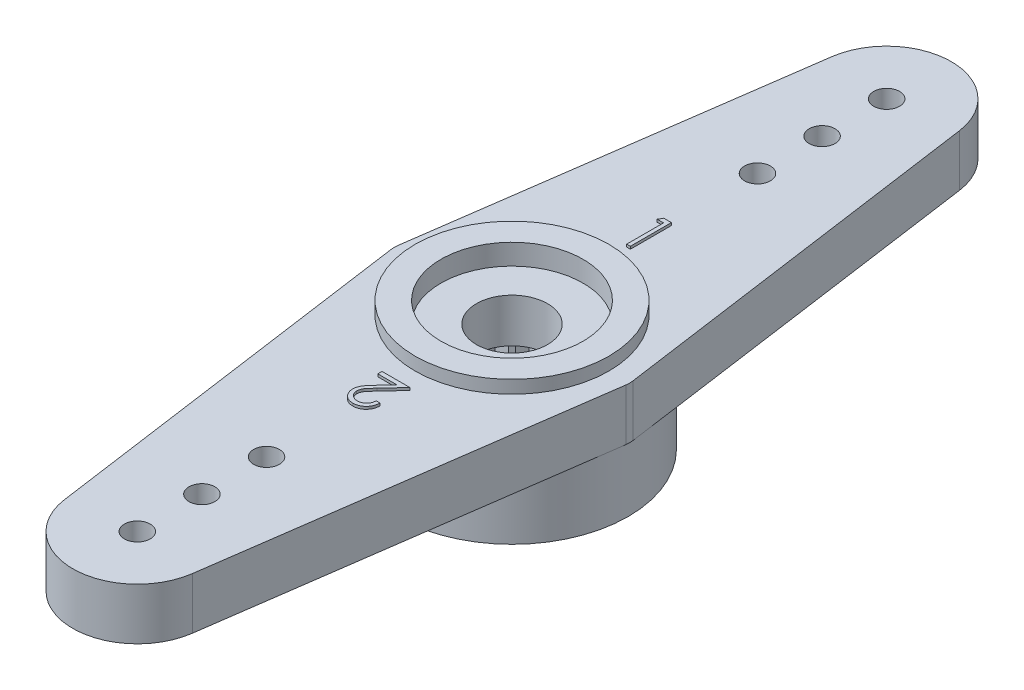
SolidWorks part; units mm, degrees
ref_plane "Front Plane" through (0, 0, 0) normal (0, 0, 1) x (1, 0, 0)
ref_plane "Top Plane" through (0, 0, 0) normal (0, 1, 0) x (1, 0, 0)
ref_plane "Right Plane" through (0, 0, 0) normal (1, 0, 0) x (0, 0, -1)
sketch "Sketch1" plane through (0, 0, 0) normal (0, 1, 0) x (1, 0, 0)
  line L0 (0, 17) -> (0, -17) construction
  line L1 (-17, 0) -> (17, 0) construction
  line L2 (-2.6883, 13.3345) -> (-4.0139, 3.9009) construction
  line L3 (4, -4) -> (-4, -4) construction
  line L4 (4, -4) -> (4, 4) construction
  line L5 (4, 4) -> (-4, 4) construction
  line L6 (-4, -4) -> (-4, 4) construction
  line L7 (4, -4) -> (-4, 4) construction
  line L8 (4, 4) -> (-4, -4) construction
  line L9 (-4, 4) -> (-2.4757, 14.8479)
  line L10 (4, 4) -> (2.4757, 14.8479)
  line L11 (4, -4) -> (2.4757, -14.8479)
  line L12 (-4, -4) -> (-2.4757, -14.8479)
  line L13 (-4, 4) -> (-4.5621, 0)
  line L14 (4, 4) -> (4.5621, 0)
  line L15 (4, -4) -> (4.5621, 0)
  line L16 (-4, -4) -> (-4.5621, 0)
  circle A0 centre (0, 0) radius 17 construction
  circle A1 centre (0, 0) radius 16 construction
  arc A2 (2.4757, 14.8479) -> (-2.4757, 14.8479) centre (0, 14.5) ccw
  arc A3 (2.4757, -14.8479) -> (-2.4757, -14.8479) centre (0, -14.5) cw
  circle A4 centre (0, -9.5) radius 0.5
  circle A5 centre (0, -12) radius 0.5
  circle A6 centre (0, 0) radius 14.5 construction
  circle A7 centre (0, 0) radius 12 construction
  circle A8 centre (0, 0) radius 9.5 construction
  circle A9 centre (0, 14.5) radius 0.5
  circle A10 centre (0, 12) radius 0.5
  circle A11 centre (0, 9.5) radius 0.5
  circle A12 centre (0, -14.5) radius 0.5
  circle A21 centre (0, 0) radius 1.375
  point P13 (-4.5621, 0)
  point P59 (0, 0)
  dimension "D1" = 34
  dimension "D2" = 1
  dimension "D3" = 5
  dimension "D4" = 24
  dimension "D5" = 8
  dimension "D6" = 8
  dimension "D7" = 19
  dimension "D9" = 29
  dimension "D11" = 1
  dimension "D12" = 1
  dimension "D13" = 1
  dimension "D8" = 1
  dimension "D10" = 1
  dimension "D14" = 2.75
  dimension "D15" = 1
extrude "Boss-Extrude1" add sketch "Sketch1" along normal blind 2
sketch "Sketch2" plane through (0, 2, 0) normal (0, 1, 0) x (1, 0, 0)
  circle A0 centre (0, 0) radius 3.75
  circle A1 centre (0, 0) radius 2.75
  dimension "D1" = 7.5
  dimension "D2" = 1
extrude "Boss-Extrude2" add sketch "Sketch2" along normal blind 0.5
sketch "Sketch3" plane through (0, 2.5, 0) normal (0, 1, 0) x (1, 0, 0)
  circle A2 centre (0, 0) radius 1.375
  circle A3 centre (0, 0) radius 2.75
  circle A5 centre (0, 0) radius 2.75
  circle A6 centre (0, 0) radius 2.75
  circle M6 centre (0, 0) radius 2.75
  dimension "D1" = 0
extrude "Cut-Extrude1" cut sketch "Sketch3" against normal blind 0.8 contours A2 M6
sketch "Sketch4" plane through (0, 0, 0) normal (0, -1, 0) x (1, 0, 0)
  circle A0 centre (0, 0) radius 4.5
  circle A1 centre (0, 0) radius 2.5
  dimension "D1" = 9
  dimension "D2" = 2
extrude "Boss-Extrude3" add sketch "Sketch4" along normal blind 2.5
sketch "Sketch5" plane through (0, -2.5, 0) normal (0, -1, 0) x (1, 0, 0)
  line L0 (0, 0) -> (0, 0.6245) construction
  line L1 (0, 3) -> (-0.299, 2.4821)
  line L2 (0, 3) -> (0.299, 2.4821)
  line L3 (0.9271, 2.8532) -> (0.4826, 2.453)
  line L4 (0.9271, 2.8532) -> (1.0514, 2.2682)
  line L5 (1.7634, 2.4271) -> (1.217, 2.1838)
  line L6 (1.7634, 2.4271) -> (1.7008, 1.8323)
  line L7 (2.4271, 1.7634) -> (1.8323, 1.7008)
  line L8 (2.4271, 1.7634) -> (2.1838, 1.217)
  line L9 (2.8532, 0.9271) -> (2.2682, 1.0514)
  line L10 (2.8532, 0.9271) -> (2.453, 0.4826)
  line L11 (3, 0) -> (2.4821, 0.299)
  line L12 (3, 0) -> (2.4821, -0.299)
  line L13 (2.8532, -0.9271) -> (2.453, -0.4826)
  line L14 (2.8532, -0.9271) -> (2.2682, -1.0514)
  line L15 (2.4271, -1.7634) -> (2.1838, -1.217)
  line L16 (2.4271, -1.7634) -> (1.8323, -1.7008)
  line L17 (1.7634, -2.4271) -> (1.7008, -1.8323)
  line L18 (1.7634, -2.4271) -> (1.217, -2.1838)
  line L19 (0.9271, -2.8532) -> (1.0514, -2.2682)
  line L20 (0.9271, -2.8532) -> (0.4826, -2.453)
  line L21 (0, -3) -> (0.299, -2.4821)
  line L22 (0, -3) -> (-0.299, -2.4821)
  line L23 (-0.9271, -2.8532) -> (-0.4826, -2.453)
  line L24 (-0.9271, -2.8532) -> (-1.0514, -2.2682)
  line L25 (-1.7634, -2.4271) -> (-1.217, -2.1838)
  line L26 (-1.7634, -2.4271) -> (-1.7008, -1.8323)
  line L27 (-2.4271, -1.7634) -> (-1.8323, -1.7008)
  line L28 (-2.4271, -1.7634) -> (-2.1838, -1.217)
  line L29 (-2.8532, -0.9271) -> (-2.2682, -1.0514)
  line L30 (-2.8532, -0.9271) -> (-2.453, -0.4826)
  line L31 (-3, 0) -> (-2.4821, -0.299)
  line L32 (-3, 0) -> (-2.4821, 0.299)
  line L33 (-2.8532, 0.9271) -> (-2.453, 0.4826)
  line L34 (-2.8532, 0.9271) -> (-2.2682, 1.0514)
  line L35 (-2.4271, 1.7634) -> (-2.1838, 1.217)
  line L36 (-2.4271, 1.7634) -> (-1.8323, 1.7008)
  line L37 (-1.7634, 2.4271) -> (-1.7008, 1.8323)
  line L38 (-1.7634, 2.4271) -> (-1.217, 2.1838)
  line L39 (-0.9271, 2.8532) -> (-1.0514, 2.2682)
  line L40 (-0.9271, 2.8532) -> (-0.4826, 2.453)
  circle A0 centre (0, 0) radius 2.5 construction
  arc A1 (-2.1838, 1.217) -> (-2.2682, 1.0514) centre (0, 0) ccw
  arc A2 (-1.7008, 1.8323) -> (-1.8323, 1.7008) centre (0, 0) ccw
  arc A3 (-1.0514, 2.2682) -> (-1.217, 2.1838) centre (0, 0) ccw
  arc A4 (-0.299, 2.4821) -> (-0.4826, 2.453) centre (0, 0) ccw
  arc A5 (0.4826, 2.453) -> (0.299, 2.4821) centre (0, 0) ccw
  arc A6 (1.217, 2.1838) -> (1.0514, 2.2682) centre (0, 0) ccw
  arc A7 (1.8323, 1.7008) -> (1.7008, 1.8323) centre (0, 0) ccw
  arc A8 (2.2682, 1.0514) -> (2.1838, 1.217) centre (0, 0) ccw
  arc A9 (2.4821, 0.299) -> (2.453, 0.4826) centre (0, 0) ccw
  arc A10 (2.453, -0.4826) -> (2.4821, -0.299) centre (0, 0) ccw
  arc A11 (2.1838, -1.217) -> (2.2682, -1.0514) centre (0, 0) ccw
  arc A12 (1.7008, -1.8323) -> (1.8323, -1.7008) centre (0, 0) ccw
  arc A13 (1.0514, -2.2682) -> (1.217, -2.1838) centre (0, 0) ccw
  arc A14 (0.299, -2.4821) -> (0.4826, -2.453) centre (0, 0) ccw
  arc A15 (-0.4826, -2.453) -> (0, -2.5) centre (0, 0) ccw
  arc A16 (-1.217, -2.1838) -> (-1.0514, -2.2682) centre (0, 0) ccw
  arc A17 (-1.8323, -1.7008) -> (-1.7008, -1.8323) centre (0, 0) ccw
  arc A18 (-2.2682, -1.0514) -> (-2.1838, -1.217) centre (0, 0) ccw
  arc A19 (-2.4821, -0.299) -> (-2.453, -0.4826) centre (0, 0) ccw
  arc A20 (-2.453, 0.4826) -> (-2.4821, 0.299) centre (0, 0) ccw
  point P68 (0, 0)
  circle M5 centre (0, 0) radius 2.5
  dimension "D1" = 30
  dimension "D2" = 3
  dimension "D3" = 20
extrude "Cut-Extrude3" cut sketch "Sketch5" against normal up to surface (2.5 mm away) contours L36 L35 M5 | L34 L33 M5 | L32 L31 M5 | L30 L29 M5 | L28 L27 M5 | L26 L25 M5 | L24 L23 M5 | L0 L21 M5 | L22 L0 M5 | L20 L19 M5 | L18 L17 M5 | L16 L15 M5 | L14 L13 M5 | L12 L11 M5 | L10 L9 M5 | L8 L7 M5 | L6 L5 M5 | L4 L3 M5 | L0 L2 M5 | L0 L1 M5 | L40 L39 M5 | L38 L37 M5
sketch "Sketch6" plane through (0, 2, 0) normal (0, 1, 0) x (1, 0, 0)
  line L1 (4.5, -4.5) -> (-4.5, -4.5) construction
  line L2 (4.5, -4.5) -> (4.5, 4.5) construction
  line L3 (4.5, 4.5) -> (-4.5, 4.5) construction
  line L4 (-4.5, -4.5) -> (-4.5, 4.5) construction
  line L5 (4.5, -4.5) -> (-4.5, 4.5) construction
  line L6 (4.5, 4.5) -> (-4.5, -4.5) construction
  circle A0 centre (0, 0) radius 4.5 construction
  text T0 "1" font "Century Gothic" height in points 6
  text T2 "2" font "Century Gothic" height in points 6
  dimension "D1" = 9
  dimension "D2" = 9
  dimension "D3" = 9
extrude "Boss-Extrude4" add sketch "Sketch6" along normal blind 0.1
fillet "Fillet1" radius 1 2 edges at (-4.5621, 1, 0) (4.5621, 1, 0)
